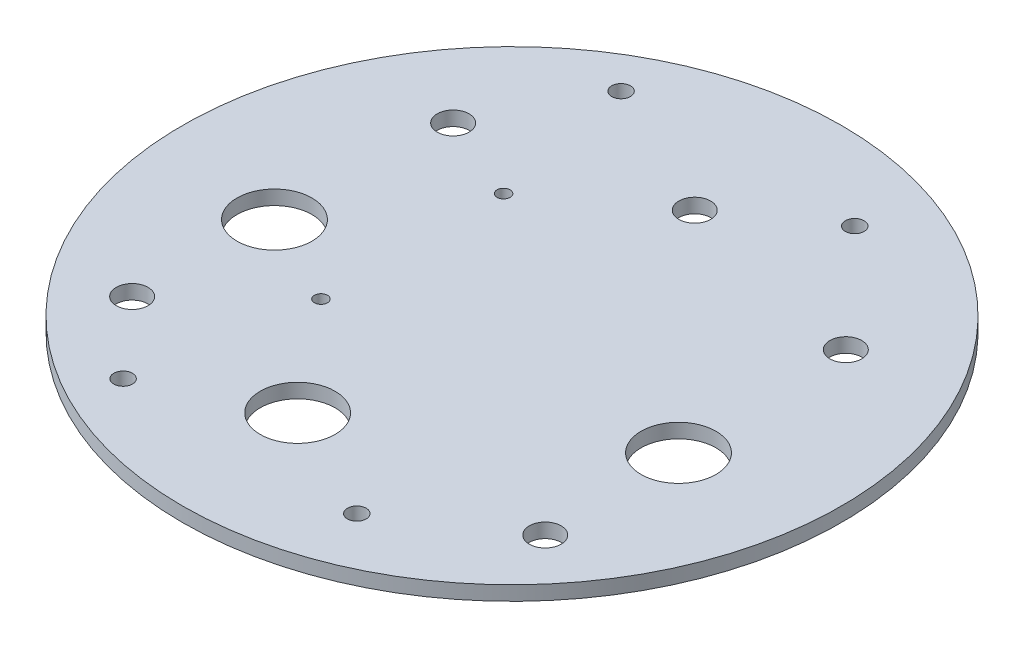
SolidWorks part; units mm, degrees
material "Stainless Steel 304"
ref_plane "Front Plane" through (0, 0, 0) normal (0, 0, 1) x (1, 0, 0)
ref_plane "Top Plane" through (0, 0, 0) normal (0, 1, 0) x (1, 0, 0)
ref_plane "Right Plane" through (0, 0, 0) normal (1, 0, 0) x (0, 0, -1)
sketch "Sketch1" plane through (0, 0, 0) normal (0, 1, 0) x (1, 0, 0)
  circle A0 centre (0, 0) radius 69.85
  dimension "D1" = 139.7
extrude "Boss-Extrude1" add sketch "Sketch1" along normal blind 3.048
sketch "Sketch6" plane through (0, 0, 0) normal (0, -1, 0) x (1, 0, 0)
  line L0 (0, 69.85) -> (0, -69.85) construction
  line L1 (-69.85, 0) -> (69.85, 0) construction
  line L2 (0, 0) -> (-53.5082, 44.8987) construction
  line L3 (0, 0) -> (53.5082, 44.8987) construction
  line L4 (0, 0) -> (57.2178, -40.0643) construction
  line L5 (0, 0) -> (-57.2178, -40.0643) construction
  circle A0 centre (0, 0) radius 69.85 construction
  point P9 (-43.7794, 36.7353)
  point P13 (43.7794, 36.7353)
  point P14 (41.6129, -29.1377)
  point P15 (-41.6129, -29.1377)
  point P16 (0, -38.735)
  dimension "D1" = 40
  dimension "D2" = 40
  dimension "D3" = 35
  dimension "D4" = 35
  dimension "D5" = 57.15
  dimension "D6" = 57.15
  dimension "D7" = 50.8
  dimension "D8" = 50.8
  dimension "D10" = 38.735
hole_wizard "17/64 (0.26563) Diameter Hole1" positions "3DSketch4" profile "Sketch7" hole size "17/64" standard "ANSI Inch"
sketch3d "3DSketch4"
  point P0 (-43.7794, 0, 36.7353)
  point P3 (43.7794, 0, 36.7353)
  point P6 (41.6129, 0, -29.1377)
  point P9 (-41.6129, 0, -29.1377)
  point P17 (0, 0, -38.735)
sketch "Sketch7" plane through (-43.7794, 0, 36.7353) normal (1, 0, 0) x (0, 0, -1)
  line L0 (0, 0) -> (0, 18.537)
  line L1 (0, 18.537) -> (3.3735, 16.51)
  line L2 (3.3735, 16.51) -> (3.3735, 0)
  line L5 (3.3735, 0) -> (0, 0)
  line L10 (0, 18.537) -> (-3.3735, 16.51) construction
  line L11 (0, -6.35) -> (0, 107.95) construction
  dimension "Hole Dia." = 6.747
  dimension "Hole Depth" = 16.51
  dimension "Drill Angle" = 118
sketch "Sketch8" plane through (0, 0, 0) normal (0, -1, 0) x (1, 0, 0)
  line L0 (0, 69.85) -> (0, -69.85) construction
  line L1 (-69.85, 0) -> (69.85, 0) construction
  line L2 (-29.6545, 52.7685) -> (-29.6545, -52.7685) construction
  line L3 (-50.6095, 52.7685) -> (50.6095, 52.7685)
  circle A0 centre (0, 0) radius 69.85 construction
  point P7 (-29.6545, 52.7685)
  point P8 (19.8755, 52.7685)
  point P9 (19.8755, -52.7685)
  point P10 (-29.6545, -52.7685)
  point P11 (-29.6545, 0)
  point P14 (0, 52.7685)
  dimension "D1" = 20.955
  dimension "D2" = 70.485
  dimension "D3" = 105.537
  dimension "D4" = 101.219
hole_wizard "5/32 (0.15625) Diameter Hole1" positions "3DSketch5" profile "Sketch9" hole size "5/32" standard "ANSI Inch"
sketch3d "3DSketch5"
  point P0 (-29.6545, 0, 52.7685)
  point P3 (19.8755, 0, 52.7685)
  point P6 (19.8755, 0, -52.7685)
  point P9 (-29.6545, 0, -52.7685)
sketch "Sketch9" plane through (-29.6545, 0, 52.7685) normal (1, 0, 0) x (0, 0, -1)
  line L0 (0, 0) -> (0, 17.7023)
  line L1 (0, 17.7023) -> (1.9844, 16.51)
  line L2 (1.9844, 16.51) -> (1.9844, 0)
  line L5 (1.9844, 0) -> (0, 0)
  line L10 (0, 17.7023) -> (-1.9844, 16.51) construction
  line L11 (0, -6.35) -> (0, 107.95) construction
  dimension "Hole Dia." = 3.9688
  dimension "Hole Depth" = 16.51
  dimension "Drill Angle" = 118
sketch "Sketch10" plane through (0, 0, 0) normal (0, -1, 0) x (1, 0, 0)
  line L0 (-43.7794, 36.7353) -> (-41.6129, -29.1377)
  line L1 (43.7794, 36.7353) -> (41.6129, -29.1377)
  line L2 (-43.7794, 36.7353) -> (43.7794, 36.7353)
  line L3 (-29.6545, 52.7685) -> (19.8755, 52.7685)
  point P0 (-4.8895, 40.5453)
  point P1 (42.8187, 7.5253)
  point P2 (-42.8187, 7.5253)
  point P3 (-4.8895, 52.7685)
  dimension "D1" = 0
  dimension "D2" = 0
  dimension "D3" = 3.81
  dimension "D4" = 29.21
  dimension "D5" = 29.21
hole_wizard "5/8 (0.625) Diameter Hole1" positions "3DSketch6" profile "Sketch11" hole size "5/8" standard "ANSI Inch"
sketch3d "3DSketch6"
  point P0 (-42.8187, 0, 7.5253)
  point P3 (-4.8895, 0, 40.5453)
  point P6 (42.8187, 0, 7.5253)
sketch "Sketch11" plane through (-42.8187, 0, 7.5253) normal (1, 0, 0) x (0, 0, -1)
  line L0 (0, 0) -> (0, 21.2793)
  line L1 (0, 21.2793) -> (7.9375, 16.51)
  line L2 (7.9375, 16.51) -> (7.9375, 0)
  line L5 (7.9375, 0) -> (0, 0)
  line L10 (0, 21.2793) -> (-7.9375, 16.51) construction
  line L11 (0, -6.35) -> (0, 107.95) construction
  dimension "Hole Dia." = 15.875
  dimension "Hole Depth" = 16.51
  dimension "Drill Angle" = 118
sketch "Sketch12" plane through (0, 0, 0) normal (0, -1, 0) x (1, 0, 0)
  line L1 (-26.4545, -24.6677) -> (18.5455, -24.6677) construction
  line L2 (-26.4545, -24.6677) -> (-26.4545, 20.3323) construction
  line L3 (-26.4545, 20.3323) -> (18.5455, 20.3323) construction
  line L4 (18.5455, -24.6677) -> (18.5455, 20.3323) construction
  circle A0 centre (-29.6545, -52.7685) radius 1.9844 construction
  circle A1 centre (-41.6129, -29.1377) radius 3.3735 construction
  point P4 (-23.3045, 17.1823)
  point P5 (-23.3045, -21.5177)
  dimension "D1" = 45
  dimension "D2" = 45
  dimension "D3" = 3.15
  dimension "D4" = 3.15
  dimension "D5" = 3.15
  dimension "D6" = 6.35
  dimension "D7" = 7.62
hole_wizard "7/64 (0.10938) Diameter Hole1" positions "3DSketch7" profile "Sketch13" hole size "7/64" standard "ANSI Inch"
sketch3d "3DSketch7"
  point P0 (-23.3045, 0, 17.1823)
  point P3 (-23.3045, 0, -21.5177)
sketch "Sketch13" plane through (-23.3045, 0, 17.1823) normal (1, 0, 0) x (0, 0, -1)
  line L0 (0, 0) -> (0, 17.3447)
  line L1 (0, 17.3447) -> (1.3891, 16.51)
  line L2 (1.3891, 16.51) -> (1.3891, 0)
  line L5 (1.3891, 0) -> (0, 0)
  line L10 (0, 17.3447) -> (-1.3891, 16.51) construction
  line L11 (0, -6.35) -> (0, 107.95) construction
  dimension "Hole Dia." = 2.7783
  dimension "Hole Depth" = 16.51
  dimension "Drill Angle" = 118
